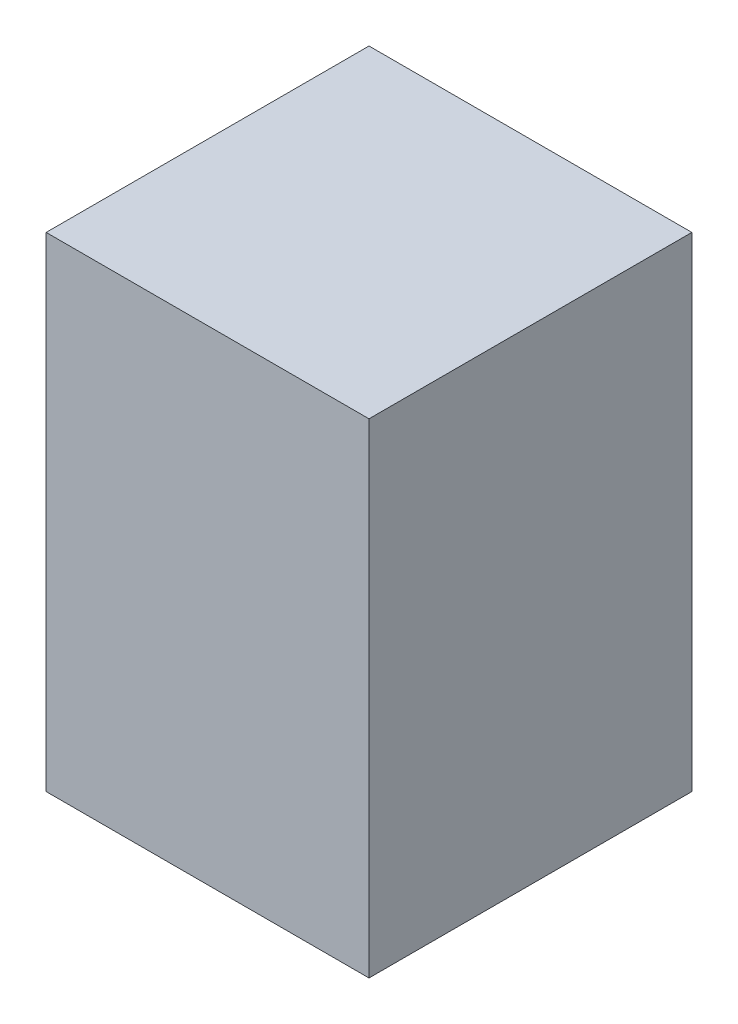
SolidWorks part; units mm, degrees
ref_plane "Front Plane" through (0, 0, 0) normal (0, 0, 1) x (1, 0, 0)
ref_plane "Top Plane" through (0, 0, 0) normal (0, 1, 0) x (1, 0, 0)
ref_plane "Right Plane" through (0, 0, 0) normal (1, 0, 0) x (0, 0, -1)
sketch "Sketch1" plane through (0, 0, 0) normal (0, 1, 0) x (1, 0, 0)
  line L1 (-2000, -2000) -> (2000, -2000)
  line L2 (-2000, -2000) -> (-2000, 2000)
  line L3 (-2000, 2000) -> (2000, 2000)
  line L4 (2000, -2000) -> (2000, 2000)
  line L5 (-2000, -2000) -> (2000, 2000) construction
  line L6 (-2000, 2000) -> (2000, -2000) construction
  point P0 (0, 0)
  dimension "D1" = 4000
  dimension "D2" = 4000
extrude "Boss-Extrude1" add sketch "Sketch1" along normal blind 6000
